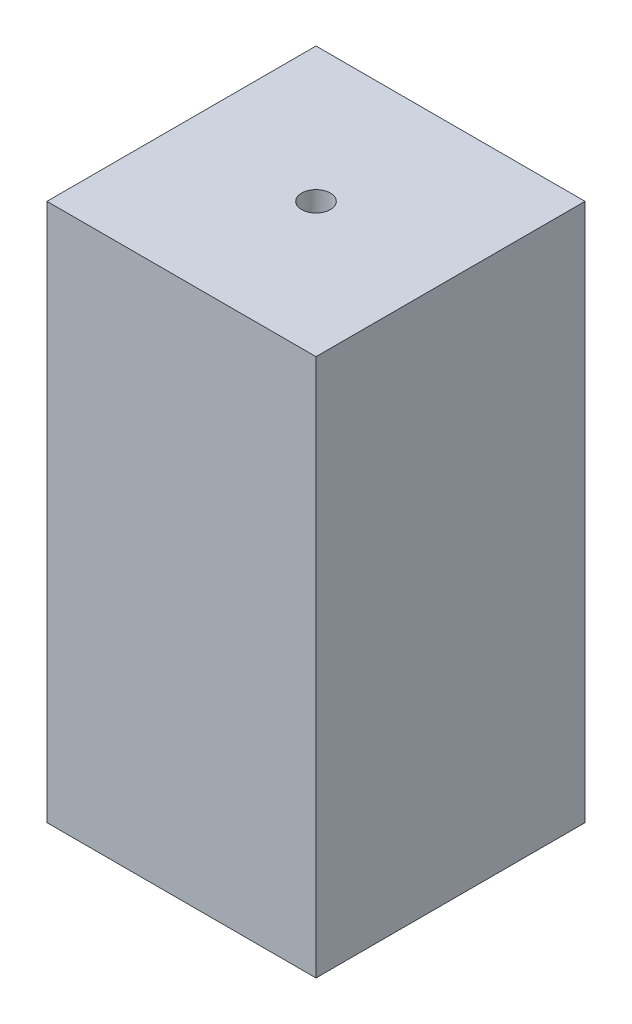
SolidWorks part; units mm, degrees
ref_plane "Alzado" through (0, 0, 0) normal (0, 0, 1) x (1, 0, 0)
ref_plane "Planta" through (0, 0, 0) normal (0, 1, 0) x (1, 0, 0)
ref_plane "Vista lateral" through (0, 0, 0) normal (1, 0, 0) x (0, 0, -1)
sketch "Croquis_base" plane through (0, 0, 0) normal (0, 1, 0) x (1, 0, 0)
  line L1 (-37.5, -37.5) -> (37.5, -37.5)
  line L2 (-37.5, -37.5) -> (-37.5, 37.5)
  line L3 (-37.5, 37.5) -> (37.5, 37.5)
  line L4 (37.5, -37.5) -> (37.5, 37.5)
  line L5 (-37.5, -37.5) -> (37.5, 37.5) construction
  line L6 (-37.5, 37.5) -> (37.5, -37.5) construction
  point P0 (0, 0)
  dimension "D1" = 37.5
extrude "Columna_75x150" add sketch "Croquis_base" along normal blind 150
sketch "Croquis_agujeros_montaje" plane through (0, 0, 0) normal (0, 1, 0) x (1, 0, 0)
  circle A0 centre (0, 0) radius 4
  dimension "D1" = 8
extrude "Agujero_inserto_M6" cut sketch "Croquis_agujeros_montaje" along normal blind 14
ref_plane "Plano_cara_superior" through (0, 150, 0) normal (0, 1, 0) x (1, 0, 0)
sketch "Croquis_agujero_superior" plane through (0, 150, 0) normal (0, 1, 0) x (1, 0, 0)
  circle A0 centre (0, 0) radius 4
  dimension "D1" = 8
extrude "Agujero_superior_M6" cut sketch "Croquis_agujero_superior" against normal blind 14
